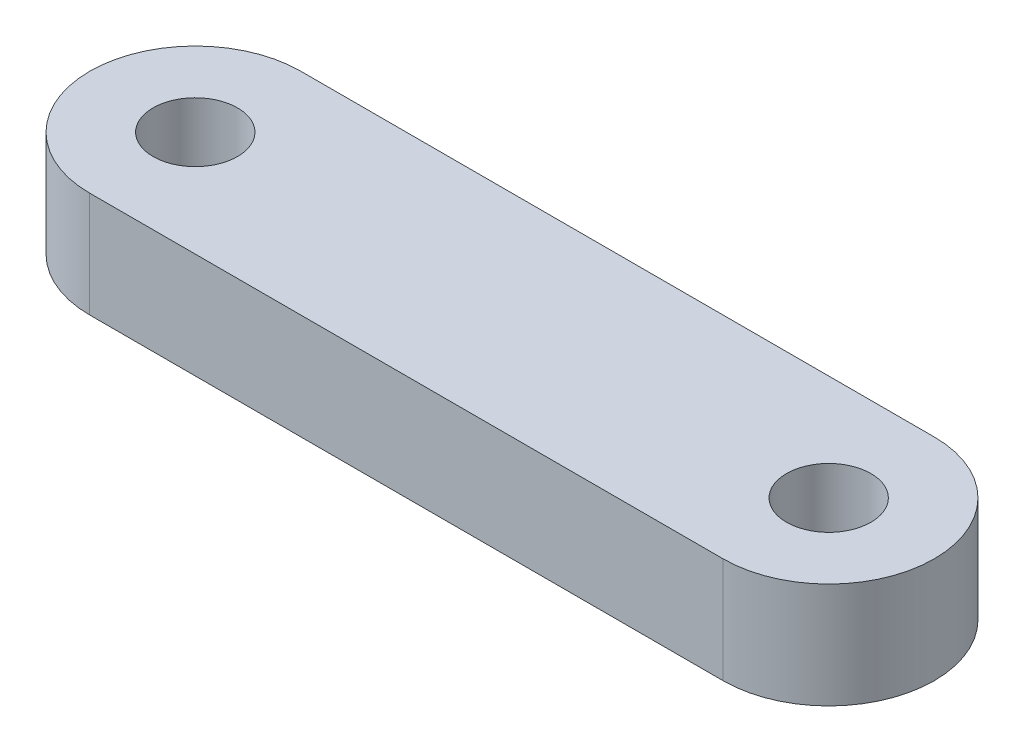
SolidWorks part; units mm, degrees
ref_plane "Front Plane" through (0, 0, 0) normal (0, 0, 1) x (1, 0, 0)
ref_plane "Top Plane" through (0, 0, 0) normal (0, 1, 0) x (1, 0, 0)
ref_plane "Right Plane" through (0, 0, 0) normal (1, 0, 0) x (0, 0, -1)
sketch "Sketch1" plane through (0, 0, 0) normal (0, 1, 0) x (1, 0, 0)
  line L0 (-47.6383, 0) -> (252.3617, 0) construction
  line L1 (-47.6383, 50) -> (252.3617, 50)
  line L2 (-47.6383, -50) -> (252.3617, -50)
  arc A0 (-47.6383, 50) -> (-47.6383, -50) centre (-47.6383, 0) ccw
  arc A1 (252.3617, -50) -> (252.3617, 50) centre (252.3617, 0) ccw
  point P3 (102.3617, 0)
extrude "Boss-Extrude1" add sketch "Sketch1" along normal blind 50
sketch "Sketch2" plane through (0, 50, 0) normal (0, 1, 0) x (1, 0, 0)
  circle A0 centre (-47.6383, 0) radius 20
  circle A1 centre (252.3617, 0) radius 20
extrude "Cut-Extrude1" cut sketch "Sketch2" against normal blind 50
